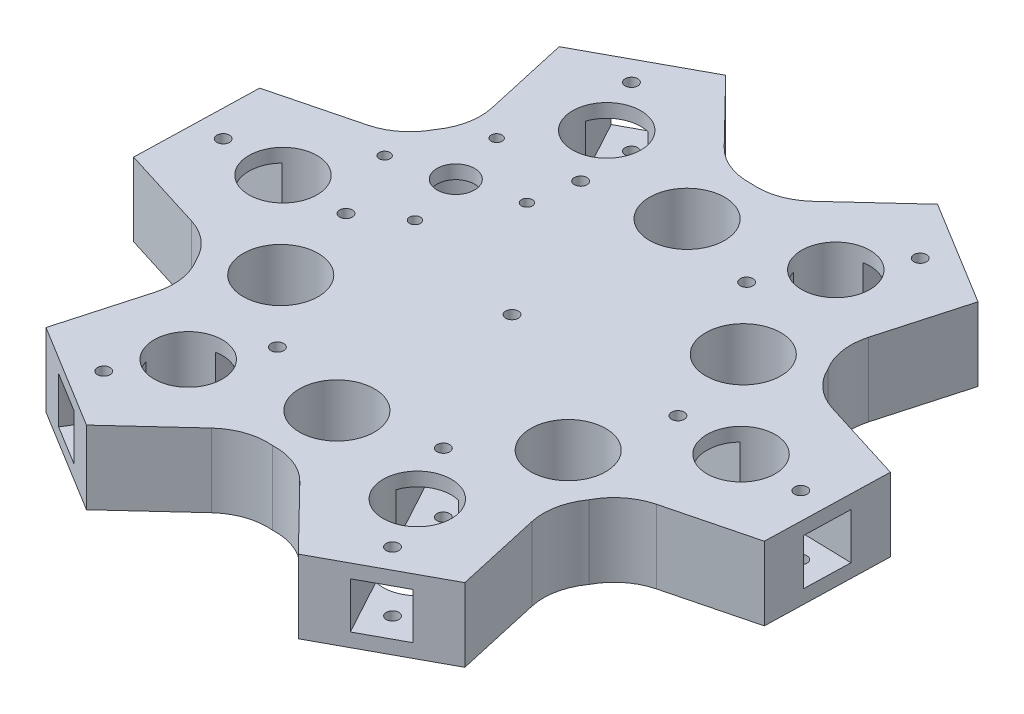
SolidWorks part; units mm, degrees
ref_plane "Alzado" through (0, 0, 0) normal (0, 0, 1) x (1, 0, 0)
ref_plane "Planta" through (0, 0, 0) normal (0, 1, 0) x (1, 0, 0)
ref_plane "Vista lateral" through (0, 0, 0) normal (1, 0, 0) x (0, 0, -1)
sketch "Croquis2" plane through (0, 0, 0) normal (0, 1, 0) x (1, 0, 0)
  line L0 (-14.424, -110.7546) -> (9.8666, -107.5585) construction
  line L1 (0, 0) -> (55.8116, 90.9663) construction
  line L2 (34.3385, 90.3873) -> (65.0234, 71.5609)
  line L3 (0, 0) -> (93.8174, 50.8733) construction
  line L4 (0, 0) -> (106.6849, -2.8511) construction
  line L5 (0, 0) -> (90.9663, -55.8116) construction
  line L6 (0, 0) -> (50.8733, -93.8174) construction
  line L7 (0, 0) -> (-2.8511, -106.6849) construction
  line L8 (0, 0) -> (-55.8116, -90.9663) construction
  line L9 (0, 0) -> (-93.8174, -50.8733) construction
  line L10 (0, 0) -> (-106.6849, 2.8511) construction
  line L11 (0, 0) -> (-90.9663, 55.8116) construction
  line L12 (0, 0) -> (-50.8733, 93.8174) construction
  line L13 (0, 0) -> (2.8511, 106.6849) construction
  line L14 (65.0234, 71.5609) -> (57.9987, 46.5578)
  line L15 (34.3385, 90.3873) -> (15.2308, 72.7977)
  line L16 (95.447, 15.4557) -> (70.6601, 23.2086)
  line L17 (95.447, 15.4557) -> (94.4852, -20.5315)
  line L18 (94.4852, -20.5315) -> (69.3196, -26.9494)
  line L19 (61.1085, -74.9317) -> (55.4292, -49.5891)
  line L20 (61.1085, -74.9317) -> (29.4618, -92.0923)
  line L21 (29.4618, -92.0923) -> (11.3209, -73.5073)
  line L22 (-34.3385, -90.3873) -> (-15.2308, -72.7977)
  line L23 (-34.3385, -90.3873) -> (-65.0234, -71.5609)
  line L24 (-65.0234, -71.5609) -> (-57.9987, -46.5578)
  line L25 (-95.447, -15.4557) -> (-70.6601, -23.2086)
  line L26 (-95.447, -15.4557) -> (-94.4852, 20.5315)
  line L27 (-94.4852, 20.5315) -> (-69.3196, 26.9494)
  line L28 (-61.1085, 74.9317) -> (-55.4292, 49.5891)
  line L29 (-61.1085, 74.9317) -> (-29.4618, 92.0923)
  line L30 (-29.4618, 92.0923) -> (-11.3209, 73.5073)
  circle A0 centre (45.4973, 74.1552) radius 1.85
  circle A1 centre (26.1479, 42.6179) radius 1.85
  circle A2 centre (36.084, 58.8128) radius 10
  circle A3 centre (0, 0) radius 1.85
  arc A4 (57.9987, 46.5578) -> (60.0714, 32.5743) centre (74.6477, 41.8802) ccw
  arc A5 (15.2308, 72.7977) -> (1.8256, 68.3105) centre (3.5182, 85.5211) cw
  circle A6 centre (43.9537, 23.8343) radius 11
  arc A7 (70.6601, 23.2086) -> (60.0714, 32.5743) centre (75.8226, 39.7137) cw
  arc A8 (69.3196, -26.9494) -> (58.2459, -35.7362) centre (73.5932, -43.7067) ccw
  circle A9 centre (68.9754, -1.8433) radius 10
  circle A10 centre (86.9689, -2.3242) radius 1.85
  circle A11 centre (49.9822, -1.3357) radius 1.85
  circle A12 centre (42.6179, -26.1479) radius 11
  arc A13 (55.4292, -49.5891) -> (58.2459, -35.7362) centre (72.3043, -45.8074) cw
  arc A14 (11.3209, -73.5073) -> (-1.8256, -68.3105) centre (-1.0545, -85.5869) ccw
  circle A15 centre (32.8913, -60.6561) radius 10
  circle A16 centre (41.4717, -76.4794) radius 1.85
  circle A17 centre (23.8343, -43.9537) radius 1.85
  circle A18 centre (-1.3357, -49.9822) radius 11
  arc A19 (-15.2308, -72.7977) -> (-1.8256, -68.3105) centre (-3.5182, -85.5211) cw
  arc A20 (-57.9987, -46.5578) -> (-60.0714, -32.5743) centre (-74.6477, -41.8802) ccw
  circle A21 centre (-36.084, -58.8128) radius 10
  circle A22 centre (-45.4973, -74.1552) radius 1.85
  circle A23 centre (-26.1479, -42.6179) radius 1.85
  circle A24 centre (-43.9537, -23.8343) radius 11
  arc A25 (-70.6601, -23.2086) -> (-60.0714, -32.5743) centre (-75.8226, -39.7137) cw
  arc A26 (-69.3196, 26.9494) -> (-58.2459, 35.7362) centre (-73.5932, 43.7067) ccw
  circle A27 centre (-68.9754, 1.8433) radius 10
  circle A28 centre (-86.9689, 2.3242) radius 1.85
  circle A29 centre (-49.9822, 1.3357) radius 1.85
  circle A30 centre (-42.6179, 26.1479) radius 11
  arc A31 (-55.4292, 49.5891) -> (-58.2459, 35.7362) centre (-72.3043, 45.8074) cw
  arc A32 (-11.3209, 73.5073) -> (1.8256, 68.3105) centre (1.0545, 85.5869) ccw
  circle A33 centre (-32.8913, 60.6561) radius 10
  circle A34 centre (-41.4717, 76.4794) radius 1.85
  circle A35 centre (-23.8343, 43.9537) radius 1.85
  circle A36 centre (1.3357, 49.9822) radius 11
  point P9 (49.6809, 80.9741)
  point P28 (0, 0)
  point P117 (0, 0)
  dimension "D4" = 3.7
  dimension "D5" = 3.7
  dimension "D8" = 20
  dimension "D10" = 3.7
  dimension "D12" = 22
  dimension "D1" = 24.5
  dimension "D2" = 36
  dimension "D3" = 95
  dimension "D6" = 87
  dimension "D7" = 50
  dimension "D9" = 18
  dimension "D13" = 50
  dimension "D11" = 12
  dimension "D14" = 6
extrude "Saliente-Extruir1" add sketch "Croquis2" along normal blind 21.5
sketch "Croquis3" plane through (45.2852, 0, 83.512) normal (0.4767, 0, 0.8791) x (0.8791, 0, -0.4767)
  line L0 (-18, 21.5) -> (18, 21.5) construction
  line L1 (-6.75, 17.5) -> (6.75, 17.5)
  line L2 (-6.75, 17.5) -> (-6.75, 4)
  line L3 (-6.75, 4) -> (6.75, 4)
  line L4 (6.75, 17.5) -> (6.75, 4)
  line L5 (-6.75, 17.5) -> (6.75, 4) construction
  line L6 (-6.75, 4) -> (6.75, 17.5) construction
  line L7 (18, 21.5) -> (18, 0) construction
  point P0 (0, 10.75)
  dimension "D1" = 13.5
  dimension "D2" = 13.5
  dimension "D3" = 4
  dimension "D4" = 11.25
extrude "Cortar-Extruir1" cut sketch "Croquis3" against normal through all
pattern_circular "MatrizC1" count 6 over 360 about axis through (0, 0, 0) along (0, 1, 0) of "Cortar-Extruir1"
sketch "Croquis4" plane through (0, 21.5, 0) normal (0, 1, 0) x (1, 0, 0)
  circle A0 centre (-42.6179, 26.1479) radius 5.5
  circle A1 centre (-42.6179, 26.1479) radius 11
  dimension "D1" = 11
extrude "Saliente-Extruir2" add sketch "Croquis4" against normal blind 4
sketch "Croquis5" plane through (0, 21.5, 0) normal (0, 1, 0) x (1, 0, 0)
  circle A0 centre (-47.0566, 42.5582) radius 1.6
  circle A1 centre (-42.6179, 26.1479) radius 5.5 construction
  circle A2 centre (-42.6179, 26.1479) radius 5.5
  circle A3 centre (-26.2076, 30.5865) radius 1.6
  circle A4 centre (-38.1793, 9.7376) radius 1.6
  circle A5 centre (-59.0283, 21.7092) radius 1.6
  point P4 (-47.0566, 42.5582)
  point P14 (-42.6179, 26.1479)
  dimension "D1" = 3.2
  dimension "D2" = 17
  dimension "D3" = 4
extrude "Cortar-Extruir2" cut sketch "Croquis5" against normal blind 10
